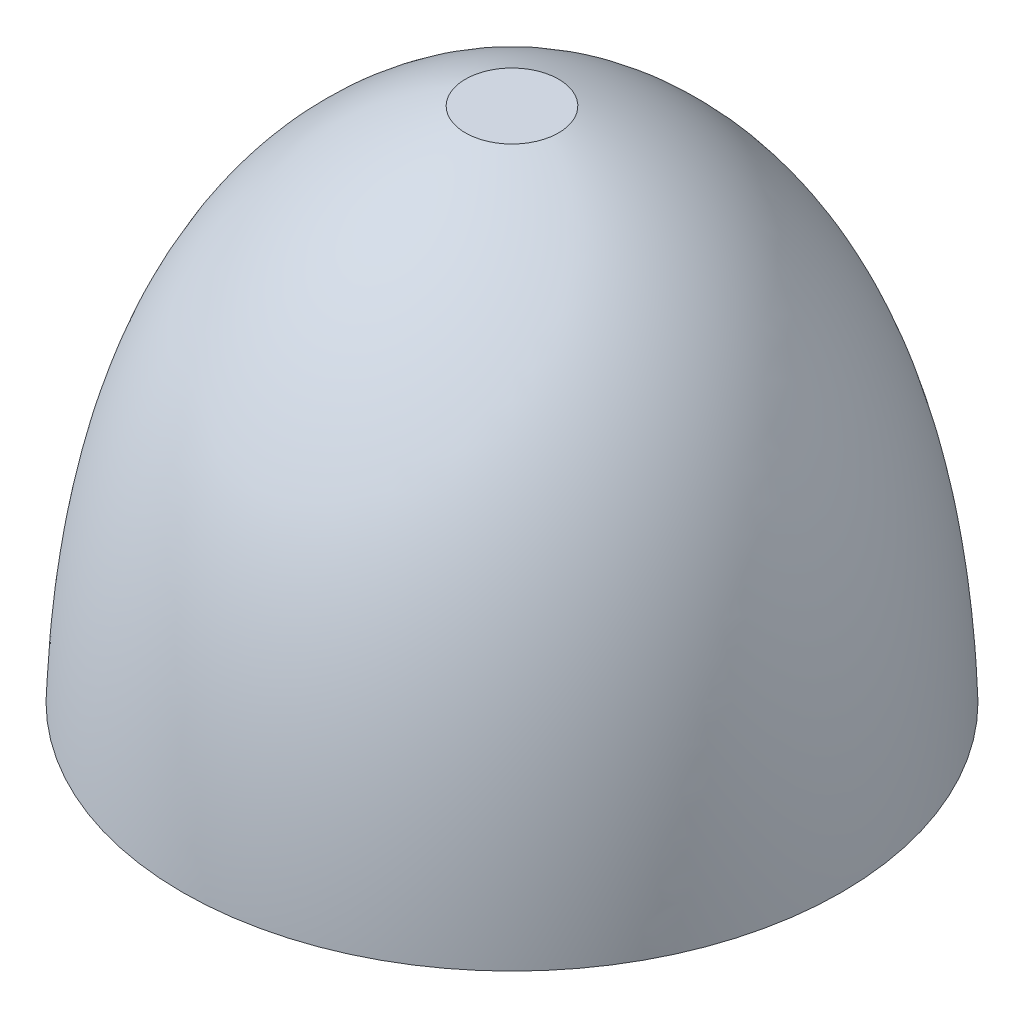
SolidWorks part; units mm, degrees
ref_plane "Front Plane" through (0, 0, 0) normal (0, 0, 1) x (1, 0, 0)
ref_plane "Top Plane" through (0, 0, 0) normal (0, 1, 0) x (1, 0, 0)
ref_plane "Right Plane" through (0, 0, 0) normal (1, 0, 0) x (0, 0, -1)
sketch "Sketch2" plane through (0, 0, 0) normal (0, 0, 1) x (1, 0, 0)
  line L0 (0, 0) -> (0, 235)
  line L1 (0, 0) -> (150, 0)
  line L2 (0, 235) -> (21.2009, 235)
  spline S0 degree 2 poles (150, 0) (143.3076, 192.9573) (21.2009, 235) knots 0 0 0 0.876123 0.876123 0.876123
  dimension "D1" = 150
  dimension "D2" = 235
revolve "Revolve1" add sketch "Sketch2" angle 360 about L0
